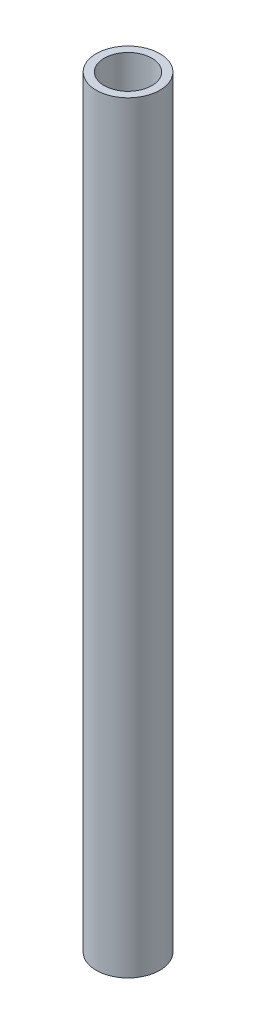
SolidWorks part; units mm, degrees
material "Rubber"
ref_plane "Front Plane" through (0, 0, 0) normal (0, 0, 1) x (1, 0, 0)
ref_plane "Top Plane" through (0, 0, 0) normal (0, 1, 0) x (1, 0, 0)
ref_plane "Right Plane" through (0, 0, 0) normal (1, 0, 0) x (0, 0, -1)
sketch "Sketch1" plane through (0, 0, 0) normal (0, 1, 0) x (1, 0, 0)
  circle A0 centre (0, 0) radius 9.525
  circle A1 centre (0, 0) radius 12.7
  dimension "D1" = 19.05
  dimension "D2" = 25.4
extrude "Boss-Extrude1" add sketch "Sketch1" along normal blind 304.8
